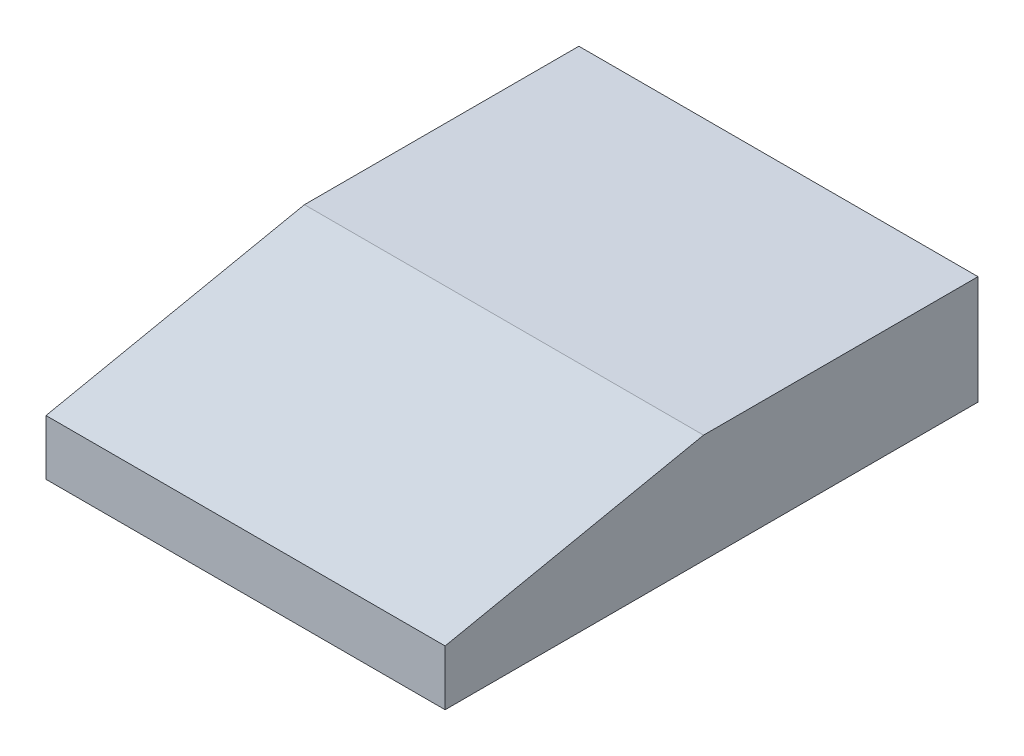
SolidWorks part; units mm, degrees
ref_plane "Front Plane" through (0, 0, 0) normal (0, 0, 1) x (1, 0, 0)
ref_plane "Top Plane" through (0, 0, 0) normal (0, 1, 0) x (1, 0, 0)
ref_plane "Right Plane" through (0, 0, 0) normal (1, 0, 0) x (0, 0, -1)
sketch "Sketch1" plane through (0, 0, 0) normal (1, 0, 0) x (0, 0, -1)
  line L0 (0, 0) -> (-64.0845, 0)
  line L1 (-64.0845, 0) -> (-64.0845, 6.6469)
  line L2 (-64.0845, 6.6469) -> (-33.0068, 13.0667)
  line L3 (-33.0068, 13.0667) -> (0, 13.0667)
  line L4 (0, 13.0667) -> (0, 0)
extrude "Boss-Extrude1" add sketch "Sketch1" along normal blind 48
